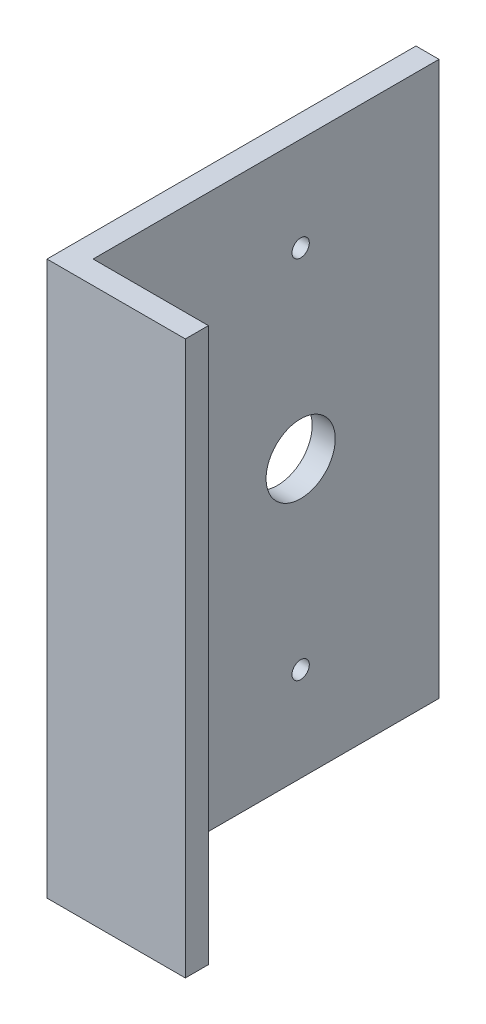
SolidWorks part; units mm, degrees
ref_plane "Front Plane" through (0, 0, 0) normal (0, 0, 1) x (1, 0, 0)
ref_plane "Top Plane" through (0, 0, 0) normal (0, 1, 0) x (1, 0, 0)
ref_plane "Right Plane" through (0, 0, 0) normal (1, 0, 0) x (0, 0, -1)
sketch "Sketch2" plane through (0, 0, 0) normal (0, 1, 0) x (1, 0, 0)
  line L0 (0, 0) -> (0, 50.8)
  line L1 (0, 0) -> (19.05, 0)
  dimension "D1" = 50.8
  dimension "D2" = 19.05
extrude "Extrude-Thin1" add sketch "Sketch2" along normal blind 76.2 thin
sketch "Sketch3" plane through (3.175, 0, 0) normal (1, 0, 0) x (0, 0, -1)
  line L1 (50.8, 76.2) -> (50.8, 0) construction
  line L2 (50.8, 76.2) -> (3.175, 76.2) construction
  line L3 (50.8, 0) -> (3.175, 0) construction
  circle A0 centre (31.75, 63.246) radius 1.1906
  circle A1 centre (31.75, 12.954) radius 1.1906
  circle A2 centre (31.75, 38.1) radius 4.7625
  point P12 (0, 0)
  dimension "D1" = 19.05
  dimension "D2" = 2.3813
  dimension "D3" = 12.954
  dimension "D4" = 19.05
  dimension "D5" = 12.954
  dimension "D6" = 2.3813
  dimension "D7" = 9.525
  dimension "D8" = 38.1
extrude "Cut-Extrude1" cut sketch "Sketch3" against normal through all
